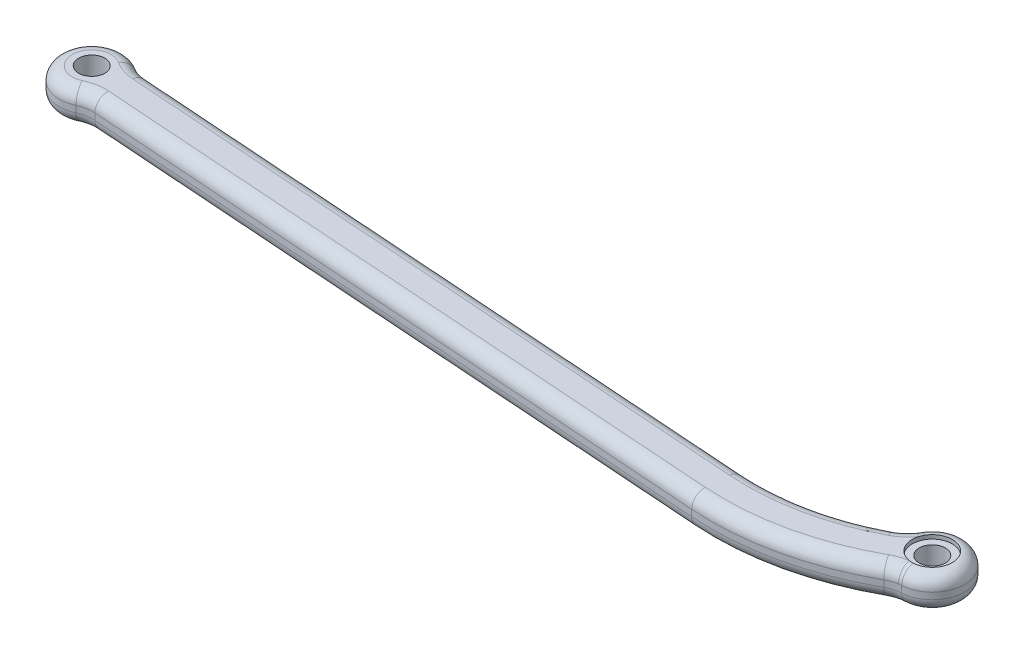
SolidWorks part; units mm, degrees
material "ABS PC"
ref_plane "Alzado" through (0, 0, 0) normal (1, 0, 0) x (0, 1, 0)
ref_plane "Planta" through (0, 0, 0) normal (0, 0, 1) x (0, 1, 0)
ref_plane "Vista lateral" through (0, 0, 0) normal (0, 1, 0) x (-1, 0, 0)
sketch "Croquis1" plane through (0, 0, 0) normal (0, 1, 0) x (-1, 0, 0)
  line L0 (0, 0) -> (260, 0) construction
  line L1 (51.8656, 14.5542) -> (260, 0) construction
  line L2 (52.3888, 22.0359) -> (260.5232, 7.4817)
  line L3 (51.3425, 7.0724) -> (259.4768, -7.4817)
  line L4 (260, 0) -> (51.8656, 14.5542) construction
  line L9 (130, -7.5) -> (130, 0) construction
  line L10 (0, 0) -> (46.2851, -65.251) construction
  line L11 (46.2851, -65.251) -> (51.8656, 14.5542) construction
  circle A0 centre (0, 0) radius 4.05
  circle A1 centre (260, 0) radius 4.05
  arc A2 (4.3392, -6.1173) -> (51.3425, 7.0724) centre (46.2851, -65.251) cw
  arc A16 (259.4768, -7.4817) -> (260.5232, 7.4817) centre (260, 0) ccw
  arc A17 (0, 0) -> (51.8656, 14.5542) centre (46.2851, -65.251) cw construction
  arc A20 (0, 0) -> (51.8656, 14.5542) centre (46.2851, -65.251) cw construction
  arc A25 (-4.3392, 6.1173) -> (4.3392, -6.1173) centre (0, 0) ccw
  arc A27 (-4.3392, 6.1173) -> (52.3888, 22.0359) centre (46.2851, -65.251) cw
  arc A28 (4.3392, -6.1173) -> (51.3425, 7.0724) centre (46.2851, -65.251) cw construction
  point P5 (0, 0)
  point P6 (0, 0)
  dimension "D3" = 8.1
  dimension "D2" = 80
  dimension "D4" = 7.5
  dimension "D1" = 260
  dimension "D5" = 4
extrude "Saliente-Extruir1" add sketch "Croquis1" along normal mid plane 10
sketch "Croquis2" plane through (0, 5, 0) normal (0, 1, 0) x (-1, 0, 0)
  circle A0 centre (260, 0) radius 4.05 construction
  circle A1 centre (0, 0) radius 4.05 construction
  circle A2 centre (260, 0) radius 4.05 construction
  circle A3 centre (0, 0) radius 4.05 construction
  circle A4 centre (0, 0) radius 10
  circle A5 centre (260, 0) radius 10
  dimension "D1" = 20
extrude "Saliente-Extruir2" add sketch "Croquis2" against normal up to surface (10 mm away) up to face at (-103.762, -5, 5.5399)
fillet "Redondeo8" radius 10 4 edges at (-9.6284, 0, -2.7007) (-252.8786, 0, -7.0203) (-253.9249, 0, 7.9431) (-1.4567, 0, 9.8933)
sketch "Croquis3" plane through (0, 5, 0) normal (0, 1, 0) x (-1, 0, 0)
  point P0 (0, 0)
hole_wizard "Refrentado para tornillo con cabeza plana de M81" positions "Croquis3" profile "Croquis4" counterbore size "M8" standard "DIN" end condition through all
sketch "Croquis4" plane through (0, 5, 0) normal (1, 0, 0) x (0, 0, 1)
  line L0 (0, 0) -> (0, 10)
  line L1 (0, 10) -> (4.05, 10)
  line L3 (4.05, 10) -> (4.05, 1.2)
  line L4 (4.05, 1.2) -> (6.2, 1.2)
  line L5 (6.2, 1.2) -> (6.2, 0)
  line L7 (6.2, 0) -> (0, 0)
  line L11 (0, -6.35) -> (0, 107.95) construction
  dimension "Diámetro de taladro hasta el siguiente" = 8.1
  dimension "Profundidad de taladro hasta el siguiente" = 10
  dimension "Diámetro de refrentado" = 12.4
  dimension "Profundidad de refrentado" = 1.2
fillet "Redondeo9" radius 4 20 edges at (-151.6266, 5, 15.0965) (-150.5802, 5, 0.1331) (-151.6266, -5, 15.0965) (-150.5802, -5, 0.1331) (-27.2982, -5, 20.1642) (-27.2982, 5, 20.1642) (-31.5224, 5, 5.7301) (-31.5224, -5, 5.7301) (-253.3804, 5, 8.2995) (-253.3804, -5, 8.2995) (-269.9756, 5, -0.6976) (-269.9756, -5, -0.6976) (-252.2897, -5, -7.2975) (-252.2897, 5, -7.2975) (-10.4738, 5, -2.6255) (-10.4738, -5, -2.6255) (8.4935, -5, -5.2783) (8.4935, 5, -5.2783) (-1.6894, -5, 10.3621) (-1.6894, 5, 10.3621)
sketch "Croquis5" plane through (0, -5, 0) normal (0, -1, 0) x (1, 0, 0)
  arc A0 (-257.4686, 5.4398) -> (-256.7361, -5.0346) centre (-260, 0) ccw construction
  point P0 (-260, 0)
hole_wizard "Refrentado para tornillo con cabeza plana de M82" positions "Croquis5" profile "Croquis6" counterbore size "M8" standard "DIN" end condition through all
sketch "Croquis6" plane through (-260, -5, 0) normal (1, 0, 0) x (0, 0, -1)
  line L0 (0, 0) -> (0, 10)
  line L1 (0, 10) -> (4.05, 10)
  line L3 (4.05, 10) -> (4.05, 1.2)
  line L4 (4.05, 1.2) -> (6.2, 1.2)
  line L5 (6.2, 1.2) -> (6.2, 0)
  line L7 (6.2, 0) -> (0, 0)
  line L11 (0, -6.35) -> (0, 107.95) construction
  dimension "Diámetro de taladro hasta el siguiente" = 8.1
  dimension "Profundidad de taladro hasta el siguiente" = 10
  dimension "Diámetro de refrentado" = 12.4
  dimension "Profundidad de refrentado" = 1.2
equation "\"L1\"=250"
equation "\"ancho\"= 15"
equation "\"esp\"= 10"
equation "\"agujeros\"=8.1"
equation "\"L2\"=260"
equation "\"D1@Croquis1\"=\"L2\""
equation "\"D3@Croquis1\"=\"agujeros\""
equation "\"D1@Saliente-Extruir1\"=\"esp\""
